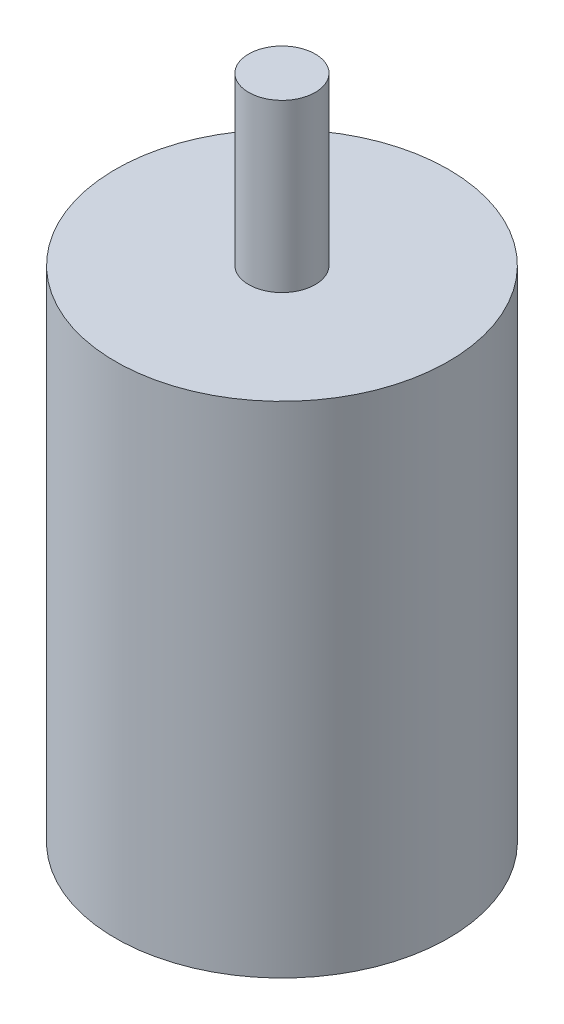
SolidWorks part; units mm, degrees
ref_plane "Front Plane" through (0, 0, 0) normal (0, 0, 1) x (1, 0, 0)
ref_plane "Top Plane" through (0, 0, 0) normal (0, 1, 0) x (1, 0, 0)
ref_plane "Right Plane" through (0, 0, 0) normal (1, 0, 0) x (0, 0, -1)
sketch "Sketch1" plane through (0, 0, 0) normal (0, 1, 0) x (1, 0, 0)
  circle A0 centre (0, 0) radius 6.35
extrude "Boss-Extrude1" add sketch "Sketch1" along normal blind 19.05
sketch "Sketch2" plane through (0, 19.05, 0) normal (0, 1, 0) x (1, 0, 0)
  circle A0 centre (0, 0) radius 1.27
extrude "Boss-Extrude2" add sketch "Sketch2" along normal blind 6.35
